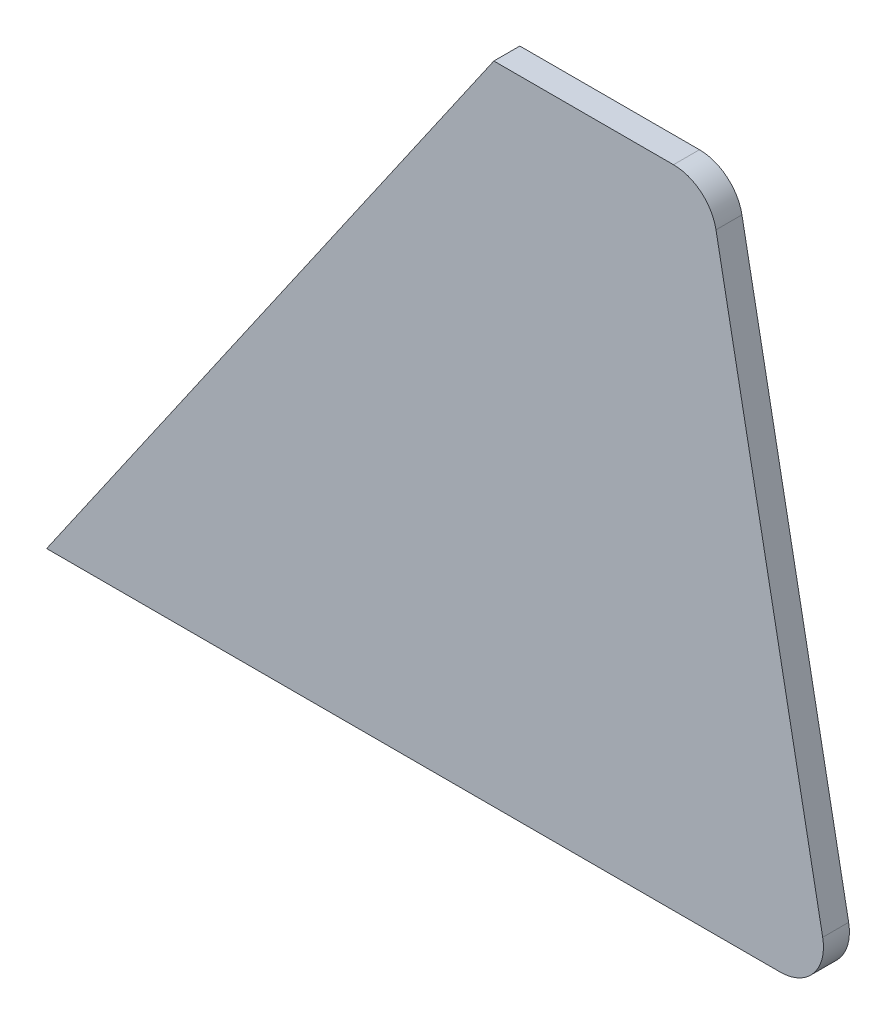
SolidWorks part; units mm, degrees
material "AISI 4340 Aço, normalizado"
ref_plane "Plano frontal" through (0, 0, 0) normal (0, 0, 1) x (1, 0, 0)
ref_plane "Plano superior" through (0, 0, 0) normal (0, 1, 0) x (1, 0, 0)
ref_plane "Plano direito" through (0, 0, 0) normal (1, 0, 0) x (0, 0, -1)
sketch "Esboço1" plane through (0, 0, 0) normal (0, 0, 1) x (1, 0, 0)
  line L0 (0, 0) -> (24.9, 0)
  line L1 (24.9, 0) -> (39.141, -74.6538)
  line L2 (39.141, -74.6538) -> (-51.6928, -74.6538)
  line L3 (-51.6928, -74.6538) -> (0, 0)
  dimension "D1" = 124.7
  dimension "D2" = 24.9
  dimension "D3" = 76
  dimension "D4" = 100.8
extrude "Ressalto-extrusão1" add sketch "Esboço1" along normal blind 3
fillet "Filete1" radius 5 2 edges at (39.141, -74.6538, 1.5) (24.9, 0, 1.5)
